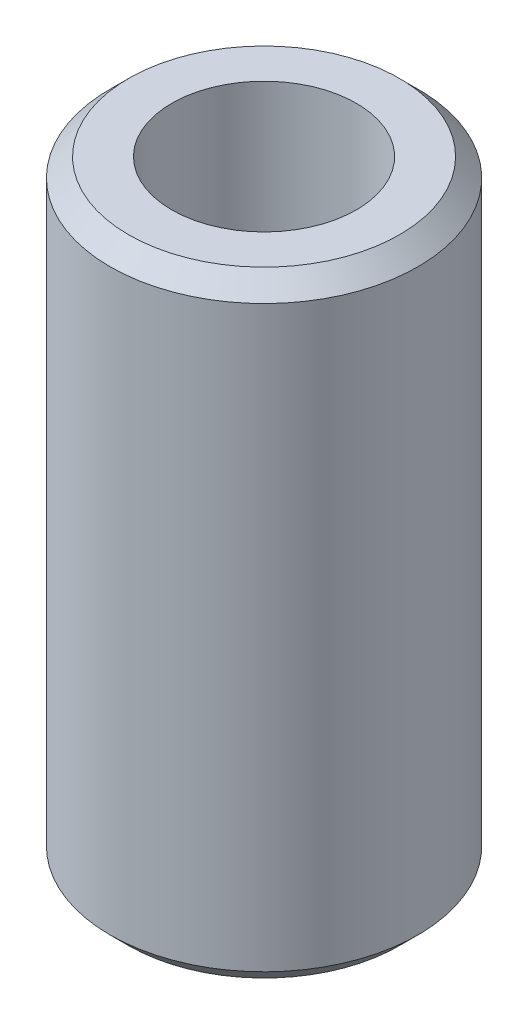
SolidWorks part; units mm, degrees
ref_plane "前视基准面" through (0, 0, 0) normal (0, 0, 1) x (1, 0, 0)
ref_plane "上视基准面" through (0, 0, 0) normal (0, 1, 0) x (1, 0, 0)
ref_plane "右视基准面" through (0, 0, 0) normal (1, 0, 0) x (0, 0, -1)
sketch "草图1" plane through (0, 0, 0) normal (0, 1, 0) x (1, 0, 0)
  circle A0 centre (0, 0) radius 2.5
  circle A1 centre (0, 0) radius 1.5
  dimension "D1" = 5
  dimension "D2" = 3
extrude "凸台-拉伸1" add sketch "草图1" along normal blind 10
chamfer "倒角1" distance 0.3 angle 45 2 edges at (0, 0, 2.5) (0, 10, 2.5)
